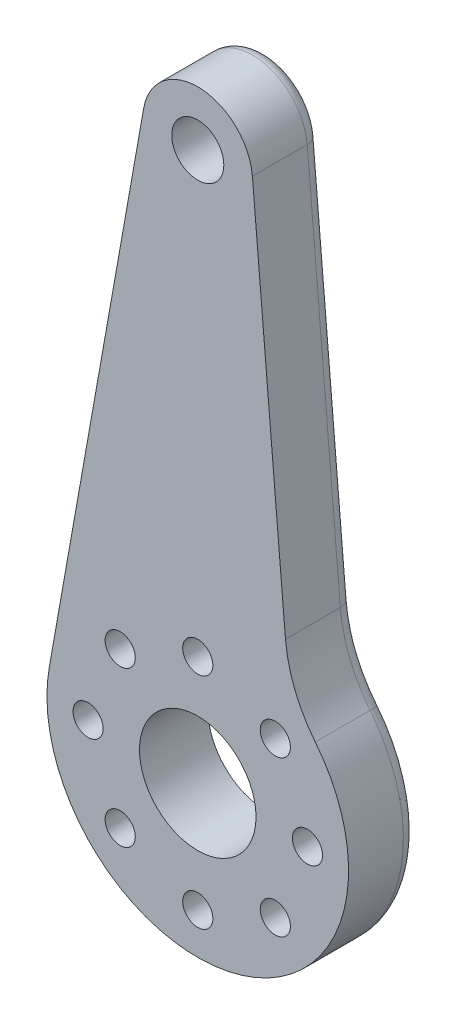
SolidWorks part; units mm, degrees
ref_plane "Front Plane" through (0, 0, 0) normal (0, 0, 1) x (1, 0, 0)
ref_plane "Top Plane" through (0, 0, 0) normal (0, 1, 0) x (1, 0, 0)
ref_plane "Right Plane" through (0, 0, 0) normal (1, 0, 0) x (0, 0, -1)
sketch "Sketch1" plane through (0, 0, 0) normal (0, 0, 1) x (1, 0, 0)
  line L0 (-18.9266, 20.3511) -> (-25.8186, -18.4239)
  line L3 (-11.0501, 20.3511) -> (-4.1581, -18.4239)
  line L4 (-14.9884, 0.8298) -> (-14.9884, 20.8298) construction
  line L5 (-14.6371, -20.3489) -> (49985.3629, -20.3489) construction
  circle A2 centre (-14.9884, 19.6511) radius 1.9
  circle A3 centre (-14.9884, -20.3489) radius 4.25
  arc A5 (-11.0501, 20.3511) -> (-18.9266, 20.3511) centre (-14.9884, 19.6511) ccw
  arc A6 (-25.8186, -18.4239) -> (-4.1581, -18.4239) centre (-14.9884, -20.3489) ccw
  circle A7 centre (-15.0314, -20.0888) radius 11 construction
  circle A8 centre (-6.9884, -20.3489) radius 1.1
  circle A9 centre (-9.3315, -26.0058) radius 1.1
  circle A10 centre (-14.9884, -28.3489) radius 1.1
  circle A11 centre (-20.6452, -26.0058) radius 1.1
  circle A12 centre (-22.9884, -20.3489) radius 1.1
  circle A13 centre (-20.6452, -14.692) radius 1.1
  circle A14 centre (-14.9884, -12.3489) radius 1.1
  circle A15 centre (-9.3315, -14.692) radius 1.1
  point P30 (-14.9884, -20.3489)
  dimension "D1" = 3.8
  dimension "D3" = 40
  dimension "D4" = 11
  dimension "D2" = 4
  dimension "D5" = 8.5
  dimension "D6" = 2.2
  dimension "D7" = 8
  dimension "D8" = 8
extrude "Boss-Extrude1" add sketch "Sketch1" along normal blind 5
sketch "Sketch2" plane through (0, 0, 5) normal (0, 0, 1) x (1, 0, 0)
  circle A0 centre (-14.9884, -20.3489) radius 11.5
  dimension "D1" = 23
extrude "Cut-Extrude1" [suppressed] cut sketch "Sketch2" against normal blind 1.75
sketch "Sketch5" plane through (0, 0, 5) normal (0, 0, 1) x (1, 0, 0)
  circle A2 centre (-14.8897, 3.8764) radius 1.55
  circle A3 centre (-14.8897, 3.8764) radius 8
extrude "Boss-Extrude2" [suppressed] add sketch "Sketch5" along normal blind 3
fillet "Fillet1" [suppressed] radius 1
sketch "Sketch4" plane through (0, 0, 0) normal (0, 0, -1) x (-1, 0, 0)
  circle A0 centre (22.9884, -20.3489) radius 1.75
  circle A1 centre (20.6452, -26.0058) radius 1.75
  circle A2 centre (14.9884, -28.3489) radius 1.75
  circle A3 centre (9.3315, -26.0058) radius 1.75
  circle A4 centre (6.9884, -20.3489) radius 1.75
  circle A5 centre (9.3315, -14.692) radius 1.75
  circle A6 centre (14.9884, -12.3489) radius 1.75
  circle A7 centre (20.6452, -14.692) radius 1.75
  circle A10 centre (14.9884, -20.3489) radius 4.25 construction
  point P20 (14.9884, -20.3489)
  dimension "D1" = 3.5
extrude "Cut-Extrude3" cut sketch "Sketch4" against normal blind 2.25
sketch "Croquis1" plane through (0, 0, 0) normal (0, 0, -1) x (-1, 0, 0)
  line L0 (11.0031, 19.9942) -> (8.28, -11.6312)
  line L1 (18.9266, 20.3511) -> (25.8186, -18.4239) construction
  line L2 (11.0501, 20.3511) -> (4.1581, -18.4239)
  arc A0 (11.0501, 20.3511) -> (11.0031, 19.9942) centre (14.9884, 19.6511) ccw
  arc A1 (4.1581, -18.4239) -> (8.28, -11.6312) centre (14.9884, -20.3489) cw
  dimension "D1" = 15
extrude "Cortar-Extruir1" cut sketch "Croquis1" against normal blind 10
fillet "Redondeo1" radius 10 1 edges at (-8.28, -11.6312, 2.5)
fillet "Redondeo2" radius 1 5 edges at (-12.2587, -31.0048, 0) (-7.9062, -10.9106, 0) (-9.796, 5.9752, 0) (-14.8084, 23.647, 0) (-22.3726, 0.9636, 0)
